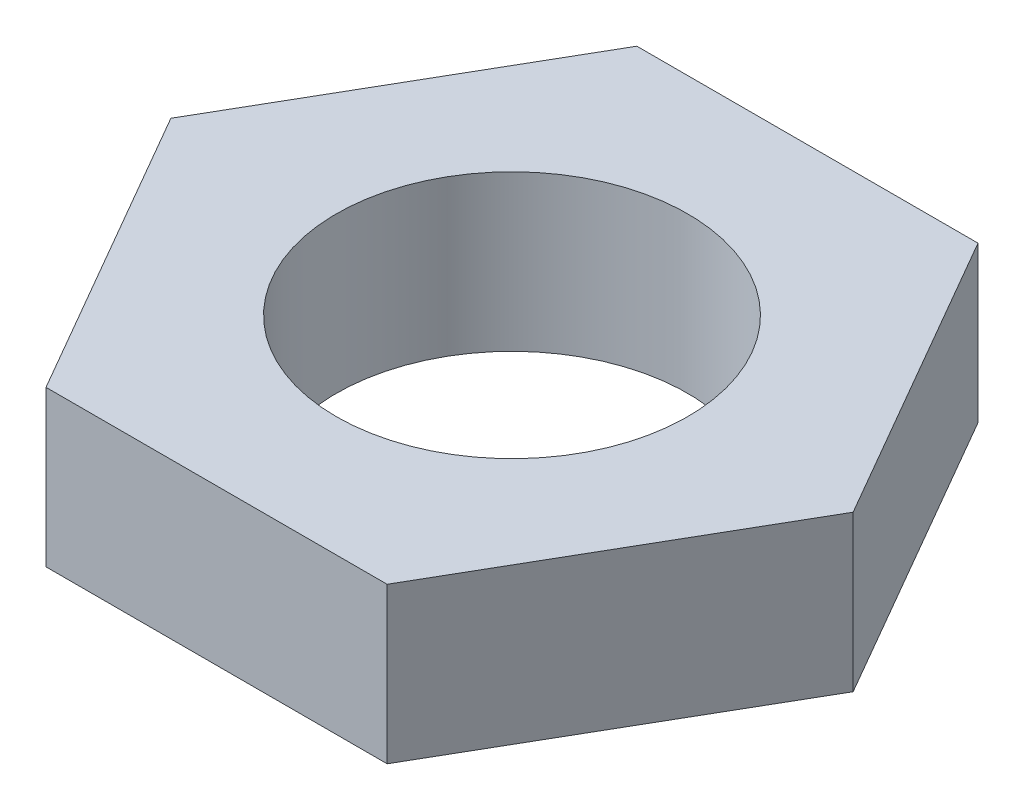
SolidWorks part; units mm, degrees
material "PE haute densité"
ref_plane "Plan de face" through (0, 0, 0) normal (0, 0, 1) x (1, 0, 0)
ref_plane "Plan de dessus" through (0, 0, 0) normal (0, 1, 0) x (1, 0, 0)
ref_plane "Plan de droite" through (0, 0, 0) normal (1, 0, 0) x (0, 0, -1)
sketch "Esquisse1" plane through (0, 0, 0) normal (0, 1, 0) x (1, 0, 0)
  line L1 (5.4848, -9.5) -> (10.9697, 0)
  line L2 (10.9697, 0) -> (5.4848, 9.5)
  line L3 (5.4848, 9.5) -> (-5.4848, 9.5)
  line L4 (-5.4848, 9.5) -> (-10.9697, 0)
  line L5 (-10.9697, 0) -> (-5.4848, -9.5)
  line L6 (-5.4848, -9.5) -> (5.4848, -9.5)
  circle A0 centre (0, 0) radius 9.5 construction
  circle A1 centre (0, 0) radius 5.65
  dimension "D2" = 11.3
  dimension "D1" = 19
extrude "Extrusion1" add sketch "Esquisse1" along normal blind 5
